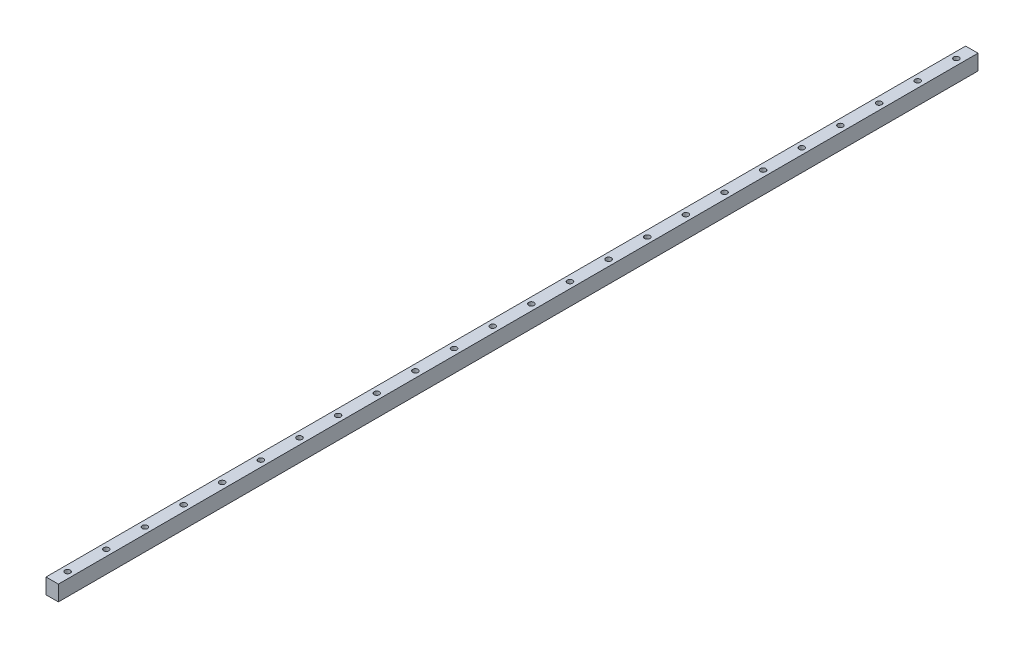
SolidWorks part; units mm, degrees
ref_plane "Front Plane" through (0, 0, 0) normal (0, 0, 1) x (1, 0, 0)
ref_plane "Top Plane" through (0, 0, 0) normal (0, 1, 0) x (1, 0, 0)
ref_plane "Right Plane" through (0, 0, 0) normal (1, 0, 0) x (0, 0, -1)
sketch "Sketch1" plane through (0, 0, 0) normal (0, 0, 1) x (1, 0, 0)
  line L1 (-4, -5) -> (4, -5)
  line L2 (-4, -5) -> (-4, 5)
  line L3 (-4, 5) -> (4, 5)
  line L4 (4, -5) -> (4, 5)
  line L5 (-4, -5) -> (4, 5) construction
  line L6 (-4, 5) -> (4, -5) construction
  point P0 (0, 0)
  dimension "D1" = 8
  dimension "D2" = 10
extrude "Boss-Extrude1" add sketch "Sketch1" along normal blind 595
sketch "Sketch2" plane through (0, 5, 0) normal (0, 1, 0) x (1, 0, 0)
  line L0 (4, 0) -> (-4, 0) construction
  circle A0 centre (0, -10) radius 1.75
  dimension "D2" = 3.5
  dimension "D1" = 10
extrude "Cut-Extrude1" cut sketch "Sketch2" against normal through all
pattern_linear "LPattern1" count 24 spacing 25 along (0, 0, 1) of "Cut-Extrude1"
